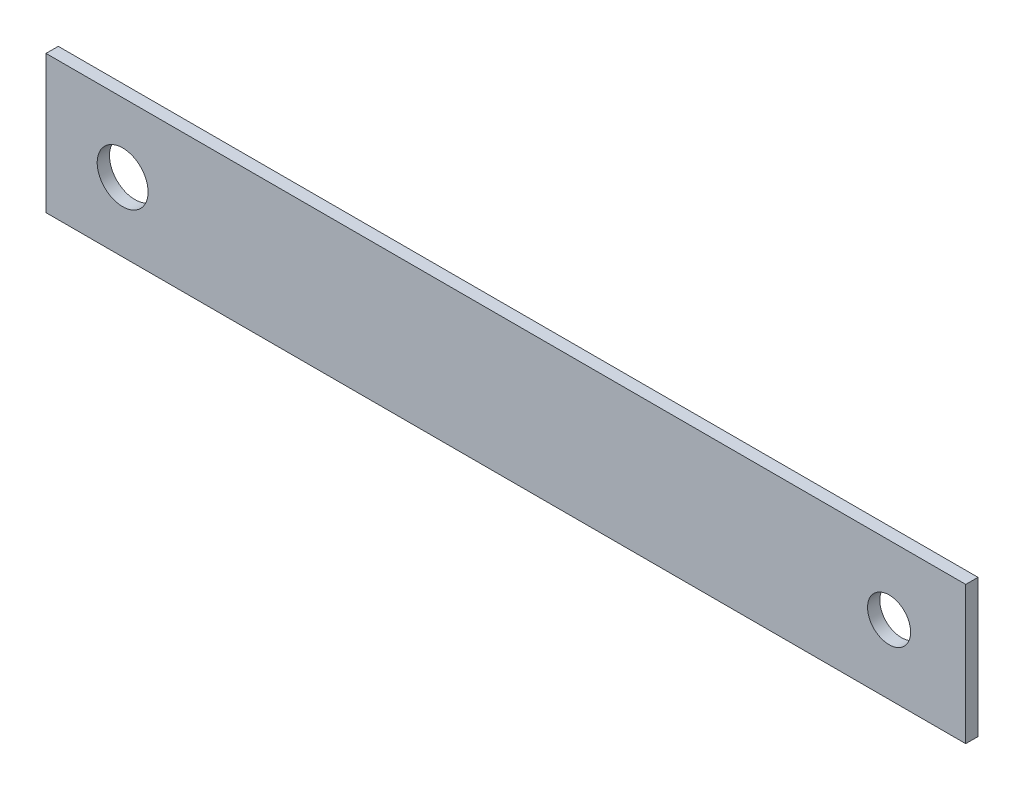
SolidWorks part; units mm, degrees
ref_plane "Front Plane" through (0, 0, 0) normal (0, 0, 1) x (1, 0, 0)
ref_plane "Top Plane" through (0, 0, 0) normal (0, 1, 0) x (1, 0, 0)
ref_plane "Right Plane" through (0, 0, 0) normal (1, 0, 0) x (0, 0, -1)
sketch "Sketch1" plane through (0, 0, 0) normal (0, 0, 1) x (1, 0, 0)
  line L1 (-6.35, 5.715) -> (69.85, 5.715)
  line L2 (-6.35, 5.715) -> (-6.35, -5.715)
  line L3 (-6.35, -5.715) -> (69.85, -5.715)
  line L4 (69.85, 5.715) -> (69.85, -5.715)
  circle A0 centre (0, 0) radius 2.1082
  circle A1 centre (63.5, 0) radius 1.7856
  point P4 (-6.35, 0)
  dimension "D4" = 4.2164
  dimension "D6" = 3.5712
  dimension "D1" = 11.43
  dimension "D2" = 6.35
  dimension "D3" = 76.2
  dimension "D5" = 6.35
extrude "Boss-Extrude1" add sketch "Sketch1" along normal blind 1.016
